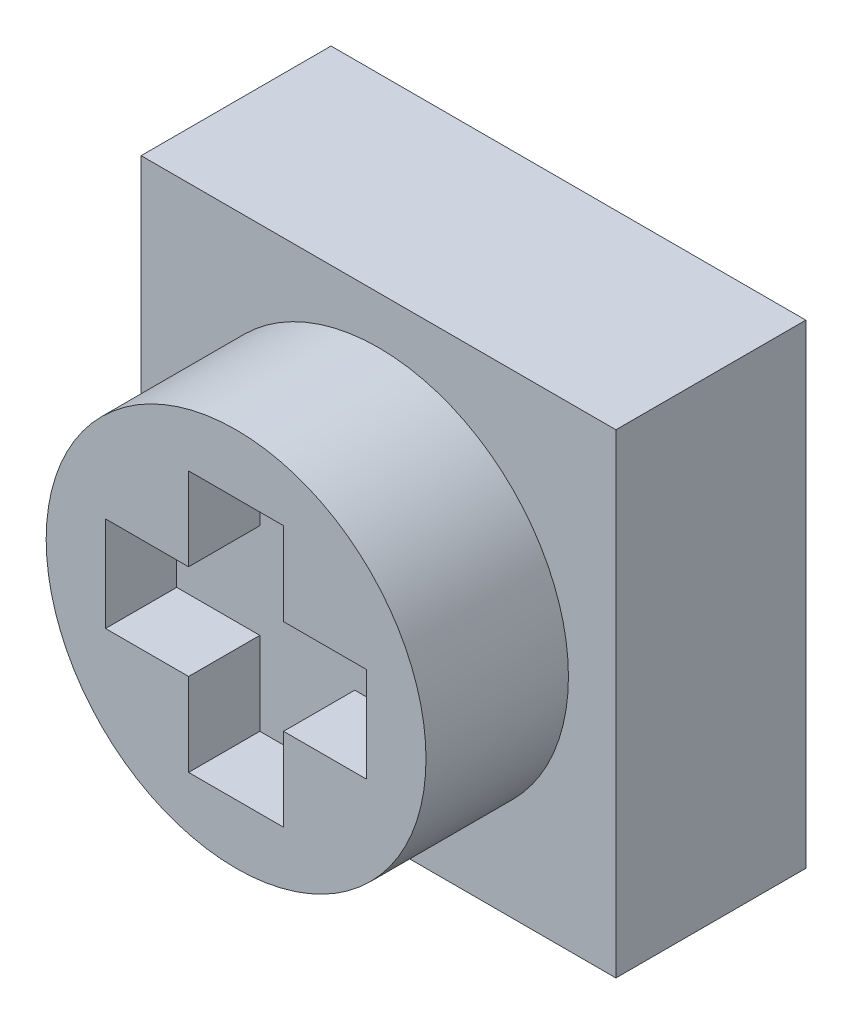
SolidWorks part; units mm, degrees
ref_plane "Front Plane" through (0, 0, 0) normal (0, 0, 1) x (1, 0, 0)
ref_plane "Top Plane" through (0, 0, 0) normal (0, 1, 0) x (1, 0, 0)
ref_plane "Right Plane" through (0, 0, 0) normal (1, 0, 0) x (0, 0, -1)
sketch "Sketch1" plane through (0, 0, 0) normal (0, 0, 1) x (1, 0, 0)
  line L1 (0, 0) -> (10, 0)
  line L2 (0, 0) -> (0, -10)
  line L3 (0, -10) -> (10, -10)
  line L4 (10, 0) -> (10, -10)
  dimension "D1" = 10
  dimension "D2" = 10
extrude "Boss-Extrude1" add sketch "Sketch1" along normal blind 4
sketch "Sketch2" plane through (0, 0, 4) normal (0, 0, 1) x (1, 0, 0)
  line L0 (0, 0) -> (10, -10) construction
  line L1 (10, -10) -> (10, 0) construction
  circle A0 centre (5, -5) radius 4
  dimension "D1" = 8
extrude "Boss-Extrude2" add sketch "Sketch2" along normal blind 3
sketch "Sketch3" plane through (0, 0, 7) normal (0, 0, 1) x (1, 0, 0)
  line L0 (4, -4) -> (4, -2.25)
  line L1 (5, -1.6211) -> (2.0738, -3.3106) construction
  line L2 (2.0738, -3.3106) -> (2.0738, -6.6894) construction
  line L3 (2.0738, -6.6894) -> (5, -8.3789) construction
  line L4 (5, -8.3789) -> (7.9262, -6.6894) construction
  line L5 (7.9262, -6.6894) -> (7.9262, -3.3106) construction
  line L6 (7.9262, -3.3106) -> (5, -1.6211) construction
  line L7 (6, -7.75) -> (4, -7.75)
  line L8 (6, -7.75) -> (6, -6)
  line L9 (6, -2.25) -> (4, -2.25)
  line L10 (4, -7.75) -> (4, -6)
  line L11 (6, -7.75) -> (4, -2.25) construction
  line L12 (6, -2.25) -> (4, -7.75) construction
  line L13 (7.75, -6) -> (6, -6)
  line L14 (7.75, -6) -> (7.75, -4)
  line L15 (7.75, -4) -> (6, -4)
  line L16 (2.25, -6) -> (2.25, -4)
  line L17 (7.75, -6) -> (2.25, -4) construction
  line L18 (7.75, -4) -> (2.25, -6) construction
  line L19 (4, -6) -> (2.25, -6)
  line L20 (6, -4) -> (6, -2.25)
  line L21 (4, -4) -> (2.25, -4)
  circle A0 centre (5, -5) radius 2.9262 construction
  dimension "D1" = 2
  dimension "D2" = 2
  dimension "D3" = 5.5
extrude "Cut-Extrude1" cut sketch "Sketch3" against normal blind 1.5
